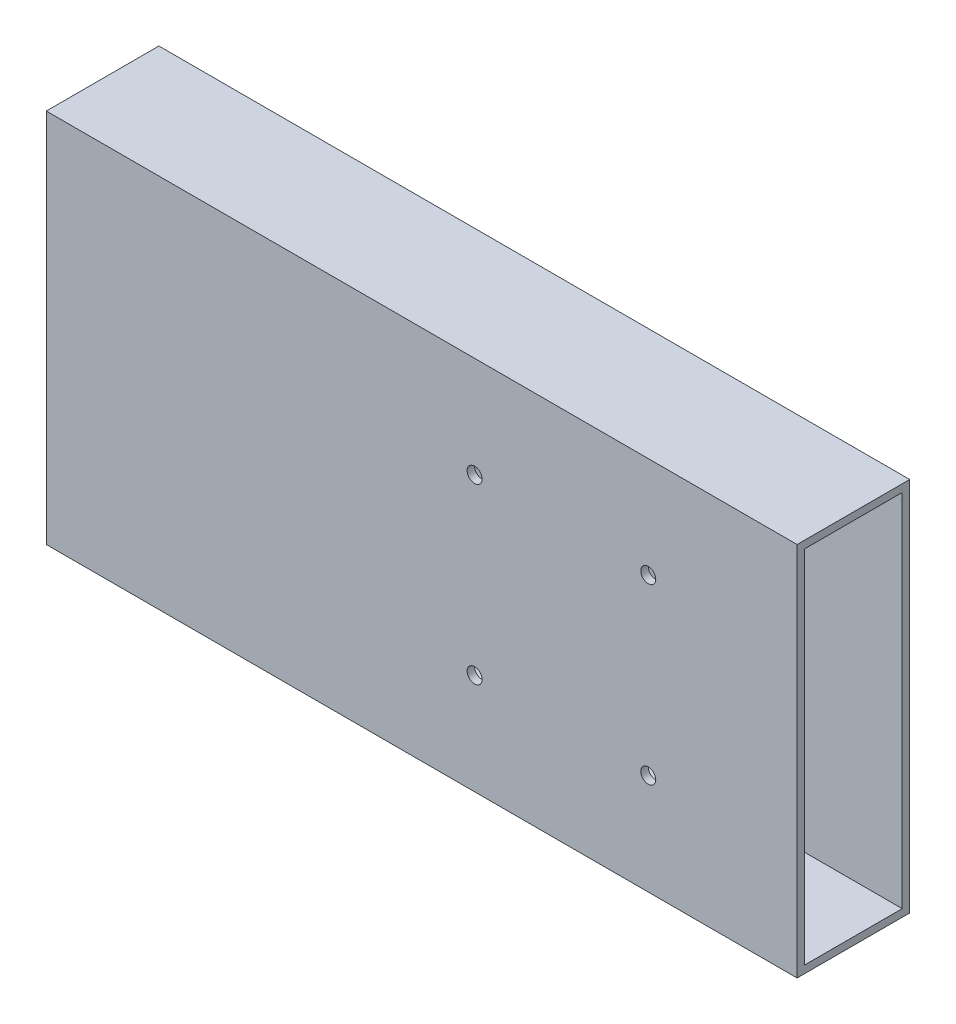
SolidWorks part; units mm, degrees
ref_plane "Ön Düzlem" through (0, 0, 0) normal (0, 0, 1) x (1, 0, 0)
ref_plane "Üst Düzlem" through (0, 0, 0) normal (0, 1, 0) x (1, 0, 0)
ref_plane "Sağ Düzlem" through (0, 0, 0) normal (1, 0, 0) x (0, 0, -1)
sketch "Çizim1" plane through (0, 0, 0) normal (0, 0, 1) x (1, 0, 0)
  line L1 (0, 0) -> (-400, 0)
  line L2 (0, 0) -> (0, 200)
  line L3 (0, 200) -> (-400, 200)
  line L4 (-400, 0) -> (-400, 200)
  dimension "D1" = 400
  dimension "D2" = 200
extrude "Yükseklik-Ekstrüzyon2" add sketch "Çizim1" along normal blind 60
shell "İç Boşaltma2" thickness 4
sketch "Çizim3" plane through (0, 0, 60) normal (0, 0, 1) x (1, 0, 0)
  line L0 (0, 100) -> (-24.7432, 100) construction
  line L1 (0, 0) -> (0, 200) construction
  line L2 (0, 200) -> (-400, 200) construction
  circle A0 centre (-79.2978, 146.25) radius 4
  circle A1 centre (-171.7978, 146.25) radius 4
  circle A2 centre (-79.2978, 53.75) radius 4
  circle A3 centre (-171.7978, 53.75) radius 4
  dimension "D1" = 92.5
  dimension "D2" = 53.75
  dimension "D3" = 8
  dimension "D4" = 8
extrude "Kes-Ekstrüzyon2" cut sketch "Çizim3" against normal up to next
